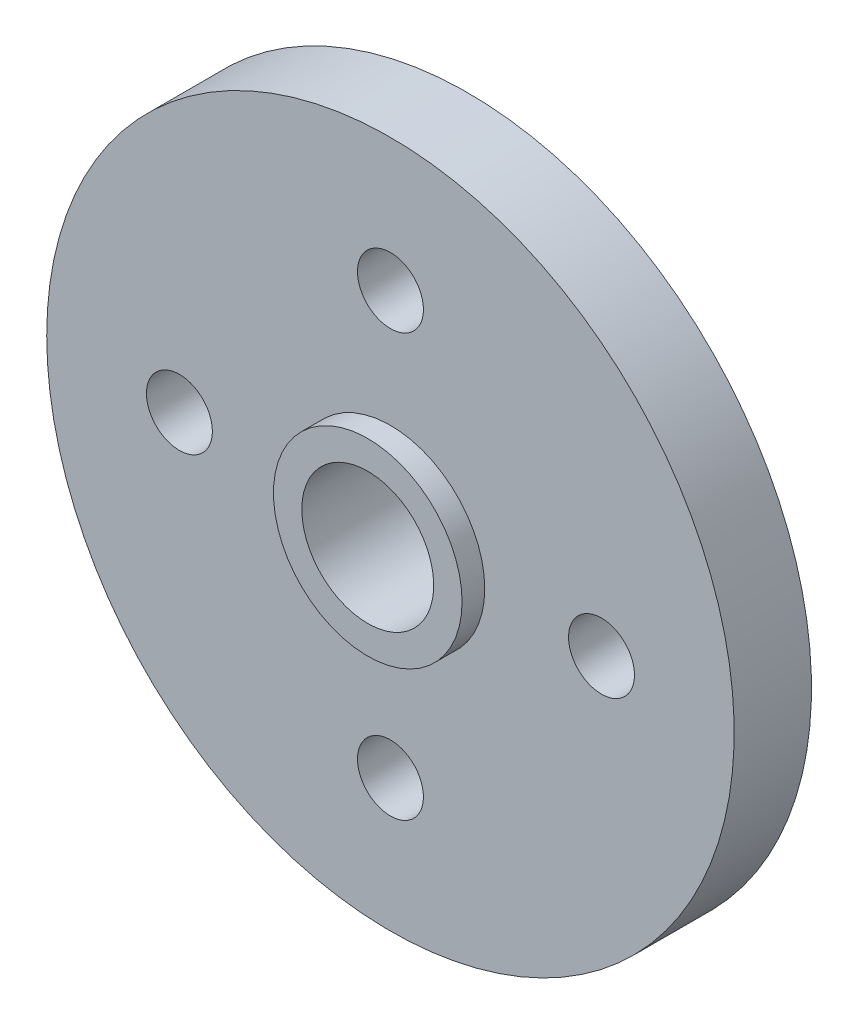
SolidWorks part; units mm, degrees
ref_plane "Piano frontale" through (0, 0, 0) normal (0, 0, 1) x (1, 0, 0)
ref_plane "Piano superiore" through (0, 0, 0) normal (0, 1, 0) x (1, 0, 0)
ref_plane "Piano destro" through (0, 0, 0) normal (1, 0, 0) x (0, 0, -1)
sketch "Schizzo1" plane through (0, 0, 0) normal (0, 0, 1) x (1, 0, 0)
  circle A0 centre (0, 0) radius 13.03
  dimension "D1" = 26.06
extrude "Estrusione-Estrusione1" add sketch "Schizzo1" along normal blind 2.93
sketch "Schizzo2" plane through (0, 0, 2.93) normal (0, 0, 1) x (1, 0, 0)
  circle A0 centre (0, 0) radius 3.575
  dimension "D1" = 7.15
extrude "Estrusione-Estrusione2" add sketch "Schizzo2" along normal blind 0.86
sketch "Schizzo3" plane through (0, 0, 0) normal (0, 0, -1) x (-1, 0, 0)
  circle A0 centre (0, 0) radius 4.725
  dimension "D1" = 9.45
extrude "Estrusione-Estrusione3" add sketch "Schizzo3" along normal blind 4.31
sketch "Schizzo4" plane through (0, 0, -4.31) normal (0, 0, -1) x (-1, 0, 0)
  circle A0 centre (0, 0) radius 2.5
  dimension "D1" = 5
extrude "Taglio-Estrusione1" cut sketch "Schizzo4" against normal through all
hole_wizard "Foro filettato M3x0.5-1" positions "Schizzo6" profile "Schizzo5" tap size "M3x0.5" standard "Ansi Metric" end condition through all
sketch "Schizzo6" plane through (0, 0, 2.93) normal (0, 0, 1) x (1, 0, 0)
  line L0 (-8, 0) -> (8, 0) construction
  line L2 (0, -8) -> (0, 8) construction
  circle A0 centre (0, 0) radius 8 construction
  point P0 (0, 8)
  point P2 (0, -8)
  point P4 (8, 0)
  point P6 (-8, 0)
  dimension "D1" = 16
sketch "Schizzo5" plane through (0, 8, 2.93) normal (1, 0, 0) x (0, -1, 0)
  line L0 (0, 0) -> (0, 7.24)
  line L1 (0, 7.24) -> (1.25, 7.24)
  line L2 (1.25, 7.24) -> (1.25, 0)
  line L5 (1.25, 0) -> (0, 0)
  line L11 (0, -6.35) -> (0, 107.95) construction
  dimension "Thru Tap Drill Dia." = 2.5
  dimension "Thru Tap Drill Depth" = 7.24
cosmetic thread "Filettatura del foro1" parameters "D2"=3
cosmetic thread "Filettatura del foro2" parameters "D2"=3
cosmetic thread "Filettatura del foro3" parameters "D2"=3
cosmetic thread "Filettatura del foro4" parameters "D2"=3
sketch "Schizzo7" plane through (0, 0, 0) normal (0, 0, -1) x (-1, 0, 0)
  line L0 (0, 5.9) -> (0, 11.075) construction
  line L1 (2.675, 9.3808) -> (2.675, 5.8399)
  line L2 (-2.675, 9.3808) -> (-2.675, 5.8399)
  line L3 (9.3808, -2.675) -> (5.8399, -2.675)
  line L4 (9.3808, 2.675) -> (5.8399, 2.675)
  line L5 (-2.675, -9.3808) -> (-2.675, -5.8399)
  line L6 (2.675, -9.3808) -> (2.675, -5.8399)
  line L7 (-9.3808, 2.675) -> (-5.8399, 2.675)
  line L8 (-9.3808, -2.675) -> (-5.8399, -2.675)
  arc A0 (-4.0398, 10.3119) -> (-10.3119, 4.0398) centre (0, 0) ccw
  arc A1 (-3.1424, 4.9935) -> (-4.9935, 3.1424) centre (0, 0) ccw
  arc A2 (-4.9935, -3.1424) -> (-3.1424, -4.9935) centre (0, 0) ccw
  arc A3 (-10.3119, -4.0398) -> (-4.0398, -10.3119) centre (0, 0) ccw
  arc A4 (3.1424, -4.9935) -> (4.9935, -3.1424) centre (0, 0) ccw
  arc A5 (4.0398, -10.3119) -> (10.3119, -4.0398) centre (0, 0) ccw
  arc A6 (4.9935, 3.1424) -> (3.1424, 4.9935) centre (0, 0) ccw
  arc A7 (10.3119, 4.0398) -> (4.0398, 10.3119) centre (0, 0) ccw
  arc A8 (2.675, 9.3808) -> (4.0398, 10.3119) centre (3.675, 9.3808) cw
  arc A9 (2.675, 5.8399) -> (3.1424, 4.9935) centre (3.675, 5.8399) ccw
  arc A10 (9.3808, 2.675) -> (10.3119, 4.0398) centre (9.3808, 3.675) ccw
  arc A11 (5.8399, 2.675) -> (4.9935, 3.1424) centre (5.8399, 3.675) cw
  arc A12 (5.8399, -2.675) -> (4.9935, -3.1424) centre (5.8399, -3.675) ccw
  arc A13 (9.3808, -2.675) -> (10.3119, -4.0398) centre (9.3808, -3.675) cw
  arc A14 (2.675, -9.3808) -> (4.0398, -10.3119) centre (3.675, -9.3808) ccw
  arc A15 (2.675, -5.8399) -> (3.1424, -4.9935) centre (3.675, -5.8399) cw
  arc A16 (-2.675, -5.8399) -> (-3.1424, -4.9935) centre (-3.675, -5.8399) ccw
  arc A17 (-2.675, -9.3808) -> (-4.0398, -10.3119) centre (-3.675, -9.3808) cw
  arc A18 (-9.3808, -2.675) -> (-10.3119, -4.0398) centre (-9.3808, -3.675) ccw
  arc A19 (-5.8399, -2.675) -> (-4.9935, -3.1424) centre (-5.8399, -3.675) cw
  arc A20 (-5.8399, 2.675) -> (-4.9935, 3.1424) centre (-5.8399, 3.675) ccw
  arc A21 (-2.675, 5.8399) -> (-3.1424, 4.9935) centre (-3.675, 5.8399) cw
  arc A22 (-2.675, 9.3808) -> (-4.0398, 10.3119) centre (-3.675, 9.3808) ccw
  arc A23 (-9.3808, 2.675) -> (-10.3119, 4.0398) centre (-9.3808, 3.675) cw
  point P25 (0, 0)
  dimension "D1" = 11.8
  dimension "D2" = 22.15
  dimension "D5" = 1
  dimension "D3" = 5.35
  dimension "D4" = 4
extrude "Taglio-Estrusione2" cut sketch "Schizzo7" against normal blind 2.1
ref_plane "Piano1" through (4.44, -1.616, 0) normal (0.9397, -0.342, 0) x (-0.342, -0.9397, 0)
hole_wizard "Foro filettato M3x0.5-2" positions "Schizzo9" profile "Schizzo8" tap size "M3x0.5" standard "Ansi Metric"
sketch "Schizzo9" plane through (4.44, -1.616, 0) normal (0.9397, -0.342, 0) x (-0.342, -0.9397, 0)
  line L0 (0, 0) -> (0, 2.155) construction
  line L1 (0, 2.155) -> (0, 4.31) construction
  line L2 (4.725, 4.31) -> (-4.725, 4.31) construction
  point P0 (0, 2.155)
sketch "Schizzo8" plane through (4.44, -1.616, -2.155) normal (0, 0, 1) x (0.342, 0.9397, 0)
  line L0 (0, 0) -> (0, 2.225)
  line L1 (0, 2.225) -> (1.25, 2.225)
  line L2 (1.25, 2.225) -> (1.25, 0)
  line L5 (1.25, 0) -> (0, 0)
  line L11 (0, -6.35) -> (0, 107.95) construction
  dimension "Thru Tap Drill Dia." = 2.5
  dimension "Thru Tap Drill Depth" = 2.225
cosmetic thread "Filettatura del foro5" parameters "D2"=3
